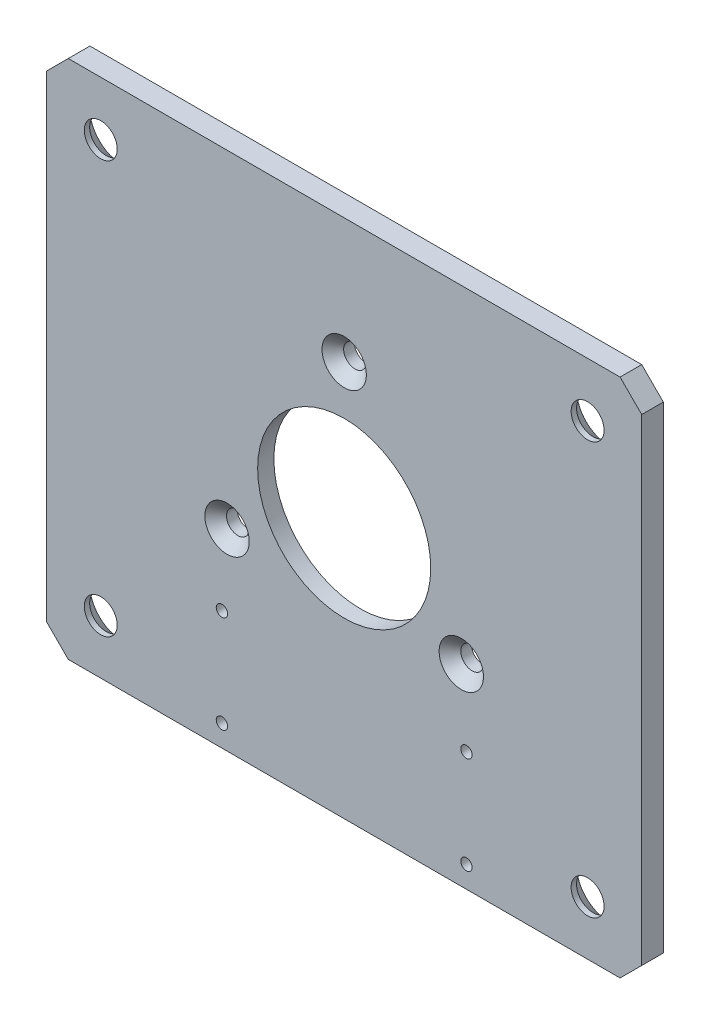
SolidWorks part; units mm, degrees
ref_plane "前视基准面" through (0, 0, 0) normal (0, 0, 1) x (1, 0, 0)
ref_plane "上视基准面" through (0, 0, 0) normal (0, 1, 0) x (1, 0, 0)
ref_plane "右视基准面" through (0, 0, 0) normal (1, 0, 0) x (0, 0, -1)
sketch "草图1" plane through (0, 0, 0) normal (0, 0, 1) x (1, 0, 0)
  line L1 (45, -38.1) -> (-45, -38.1) construction
  line L2 (45, -38.1) -> (45, 38.1) construction
  line L3 (45, 38.1) -> (-45, 38.1) construction
  line L4 (-45, -38.1) -> (-45, 38.1) construction
  line L5 (45, -38.1) -> (-45, 38.1) construction
  line L6 (45, 38.1) -> (-45, -38.1) construction
  line L7 (55, -48.1) -> (-55, -48.1)
  line L8 (55, -48.1) -> (55, 48.1)
  line L9 (55, 48.1) -> (-55, 48.1)
  line L10 (-55, -48.1) -> (-55, 48.1)
  line L11 (55, -48.1) -> (-55, 48.1) construction
  line L12 (55, 48.1) -> (-55, -48.1) construction
  circle A0 centre (-45, 38.1) radius 3.05
  circle A1 centre (-45, -38.1) radius 3.05
  circle A2 centre (45, -38.1) radius 3.05
  circle A3 centre (45, 38.1) radius 3.05
  circle A4 centre (0, 0) radius 16
  point P0 (0, 0)
  point P10 (0, 0)
  dimension "D3" = 6.1
  dimension "D6" = 32
  dimension "D1" = 90
  dimension "D2" = 76.2
  dimension "D4" = 10
  dimension "D5" = 10
extrude "凸台-拉伸1" add sketch "草图1" along normal mid plane 4
chamfer "倒角1" distance 4 angle 45 4 edges at (-55, -48.1, 0) (55, -48.1, 0) (55, 48.1, 0) (-55, 48.1, 0)
chamfer "倒角2" distance 3 angle 45 4 edges at (-41.95, -38.1, -2) (48.05, -38.1, -2) (-41.95, 38.1, -2) (48.05, 38.1, -2)
sketch "草图2" plane through (0, 0, -2) normal (0, 0, -1) x (-1, 0, 0)
  circle A0 centre (0, 0) radius 17.5
  dimension "D1" = 35
extrude "切除-拉伸1" cut sketch "草图2" against normal blind 1
sketch "草图3" plane through (0, 0, -2) normal (0, 0, -1) x (-1, 0, 0)
  circle A0 centre (0, 25) radius 2.1
  dimension "D1" = 25
  dimension "D2" = 4.2
extrude "切除-拉伸2" cut sketch "草图3" against normal through all
pattern_circular "阵列(圆周)1" count 3 over 360 about axis through (0, 0, 0) along (0, 0, 1) of "切除-拉伸2"
chamfer "倒角3" distance 2 angle 45 3 edges at (-2.1, 25, 2) (22.7006, -10.6813, 2) (-20.6006, -14.3187, 2)
sketch "草图4" plane through (0, 0, -2) normal (0, 0, -1) x (-1, 0, 0)
  line L0 (51, -48.1) -> (-51, -48.1) construction
  line L1 (22.6, -44.1) -> (-22.6, -44.1) construction
  line L2 (22.6, -44.1) -> (22.6, -26.1) construction
  line L3 (22.6, -26.1) -> (-22.6, -26.1) construction
  line L4 (-22.6, -44.1) -> (-22.6, -26.1) construction
  line L5 (22.6, -44.1) -> (-22.6, -26.1) construction
  line L6 (22.6, -26.1) -> (-22.6, -44.1) construction
  circle A0 centre (-22.6, -26.1) radius 1.05
  circle A1 centre (-22.6, -44.1) radius 1.05
  circle A2 centre (22.6, -26.1) radius 1.05
  circle A3 centre (22.6, -44.1) radius 1.05
  point P0 (0, -35.1)
  dimension "D4" = 2.1
  dimension "D1" = 18
  dimension "D2" = 45.2
  dimension "D3" = 4
extrude "切除-拉伸3" cut sketch "草图4" against normal through all
